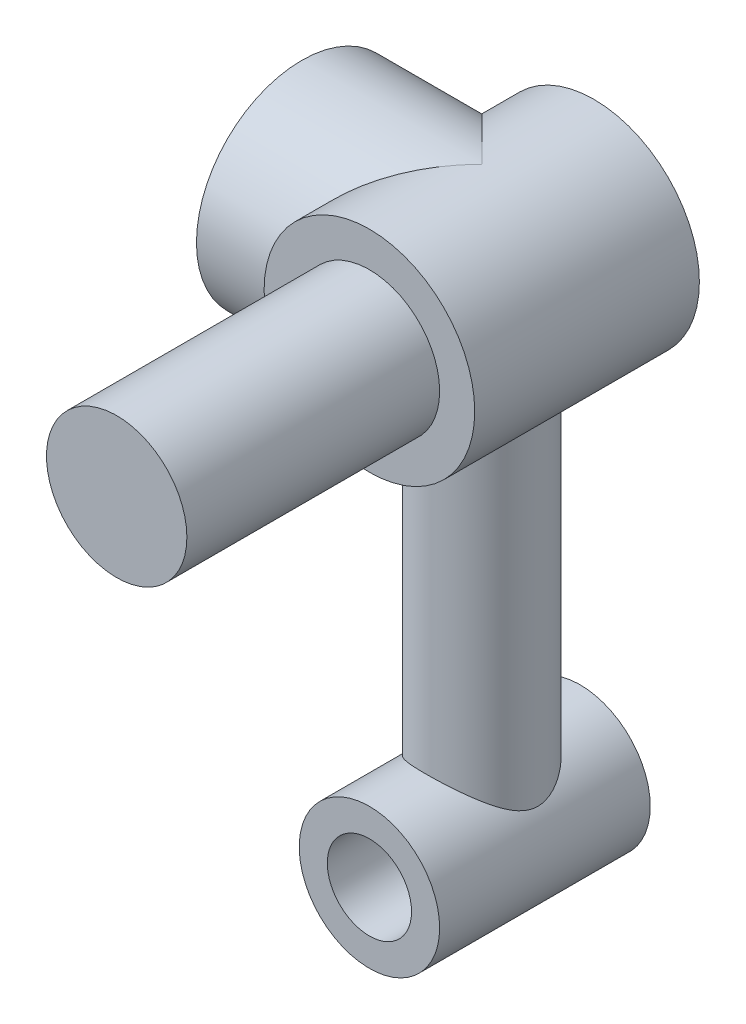
SolidWorks part; units mm, degrees
ref_plane "Front Plane" through (0, 0, 0) normal (0, 0, 1) x (1, 0, 0)
ref_plane "Top Plane" through (0, 0, 0) normal (0, 1, 0) x (1, 0, 0)
ref_plane "Right Plane" through (0, 0, 0) normal (1, 0, 0) x (0, 0, -1)
sketch "Sketch1" plane through (0, 0, 0) normal (0, 0, 1) x (1, 0, 0)
  circle A0 centre (-700, 1796) radius 50
extrude "Boss-Extrude1" add sketch "Sketch1" against normal blind 180
sketch "Sketch2" plane through (0, 0, -180) normal (0, 0, -1) x (-1, 0, 0)
  circle A0 centre (700, 1796) radius 75
  circle A1 centre (700, 1796) radius 50 construction
  dimension "D1" = 150
extrude "Boss-Extrude2" add sketch "Sketch2" along normal blind 160
ref_plane "Plane1" through (-700, 0, 0) normal (1, 0, 0) x (0, 0, -1)
sketch "Sketch3" plane through (-700, 0, 0) normal (1, 0, 0) x (0, 0, -1)
  line L0 (180, 1721) -> (340, 1721) construction
  circle A0 centre (260, 1796) radius 75
  dimension "D1" = 150
extrude "Boss-Extrude3" add sketch "Sketch3" against normal blind 128.18
ref_plane "Plane2" through (0, 1795, 0) normal (0, 1, 0) x (-1, 0, 0)
sketch "Sketch6" plane through (0, 1795, 0) normal (0, 1, 0) x (-1, 0, 0)
  line L1 (625, -180) -> (625, -340) construction
  line L2 (775, -180) -> (625, -180) construction
  line L3 (700, -180) -> (700, -260) construction
  line L4 (700, -260) -> (775, -335) construction
  line L5 (775, -185) -> (700, -260) construction
  line L6 (700, -260) -> (625, -260) construction
  circle A0 centre (700, -260) radius 40
  dimension "D1" = 80
extrude "Boss-Extrude6" [suppressed] add sketch "Sketch6" along normal blind 300
sketch "Sketch7" [suppressed] plane through (0, 0, -180) normal (0, 0, 1) x (1, 0, 0)
  line L0 (-660, 2095) -> (-740, 2095) construction
  circle A0 centre (-699.912, 2125) radius 30
  circle A1 centre (-699.912, 2125) radius 49.9296
  dimension "D1" = 60
extrude "Boss-Extrude7" [suppressed] add sketch "Sketch7" against normal blind 150
sketch "Sketch4" plane through (0, 1795, 0) normal (0, 1, 0) x (-1, 0, 0)
  line L0 (775, -180) -> (625, -180) construction
  line L1 (700, -180) -> (700, -260) construction
  line L2 (700, -260) -> (625, -260) construction
  line L3 (625, -180) -> (625, -340) construction
  circle A0 centre (700, -260) radius 40
  dimension "D1" = 80
extrude "Boss-Extrude4" add sketch "Sketch4" against normal blind 300
sketch "Sketch5" plane through (0, 0, -180) normal (0, 0, 1) x (1, 0, 0)
  line L0 (-740, 1495) -> (-660, 1495) construction
  circle A0 centre (-700, 1465) radius 30
  circle A1 centre (-700, 1465) radius 50
  dimension "D1" = 60
extrude "Boss-Extrude5" add sketch "Sketch5" against normal blind 150
